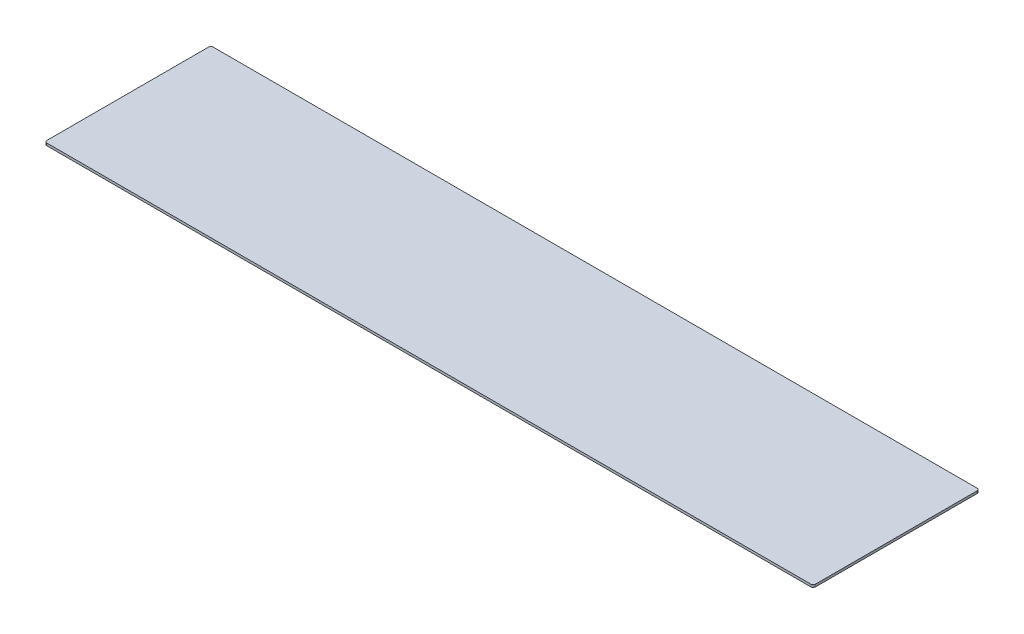
SolidWorks part; units mm, degrees
ref_plane "Alzado" through (0, 0, 0) normal (0, 0, 1) x (1, 0, 0)
ref_plane "Planta" through (0, 0, 0) normal (0, 1, 0) x (1, 0, 0)
ref_plane "Vista lateral" through (0, 0, 0) normal (1, 0, 0) x (0, 0, -1)
sketch "Croquis1" plane through (0, 0, 0) normal (0, 1, 0) x (1, 0, 0)
  line L1 (1595, -345) -> (-1595, -345)
  line L2 (1595, -345) -> (1595, 345)
  line L3 (1595, 345) -> (-1595, 345)
  line L4 (-1595, -345) -> (-1595, 345)
  line L5 (1595, -345) -> (-1595, 345) construction
  line L6 (1595, 345) -> (-1595, -345) construction
  point P0 (0, 0)
  dimension "D1" = 3190
  dimension "D2" = 690
extrude "Extruir1" add sketch "Croquis1" along normal blind 10
fillet "Redondeo1" radius 10 4 edges at (-1595, 5, -345) (1595, 5, -345) (1595, 5, 345) (-1595, 5, 345)
